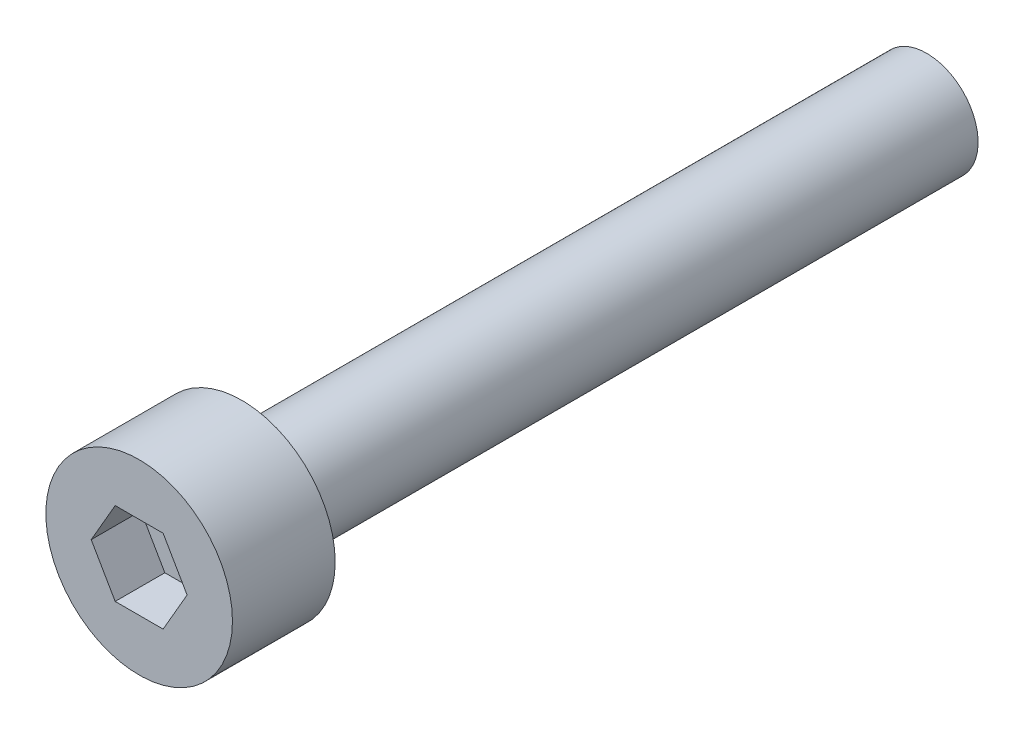
SolidWorks part; units mm, degrees
ref_plane "Front Plane" through (0, 0, 0) normal (0, 0, 1) x (1, 0, 0)
ref_plane "Top Plane" through (0, 0, 0) normal (0, 1, 0) x (1, 0, 0)
ref_plane "Right Plane" through (0, 0, 0) normal (1, 0, 0) x (0, 0, -1)
sketch "Sketch1" plane through (0, 0, 0) normal (0, 1, 0) x (1, 0, 0)
  line L0 (2.725, 3) -> (0, 3)
  line L1 (0, 3) -> (0, 0)
  line L2 (0, 0) -> (2.725, 0)
  line L3 (2.725, 0) -> (2.725, 3)
  line L4 (0, 3) -> (0, 0) construction
revolve "Revolve1" add sketch "Sketch1" angle 360 about L4
sketch "Sketch2" plane through (0, 0, -3) normal (0, 0, -1) x (-1, 0, 0)
  circle A0 centre (0, 0) radius 1.5
extrude "Boss-Extrude1" add sketch "Sketch2" along normal blind 3
sketch "Sketch3" plane through (0, 0, -6) normal (0, 0, -1) x (-1, 0, 0)
  circle A0 centre (0, 0) radius 1.5
extrude "Boss-Extrude2" add sketch "Sketch3" along normal blind 17
sketch "Sketch4" plane through (0, 0, 0) normal (0, 0, 1) x (1, 0, 0)
  line L0 (-1.4, 0) -> (-0.7, -1.2124)
  line L1 (-0.7, -1.2124) -> (0.7, -1.2124)
  line L2 (0.7, -1.2124) -> (1.4, 0)
  line L3 (1.4, 0) -> (0.7, 1.2124)
  line L4 (0.7, 1.2124) -> (-0.7, 1.2124)
  line L5 (-0.7, 1.2124) -> (-1.4, 0)
extrude "Cut-Extrude1" cut sketch "Sketch4" against normal blind 1.45
